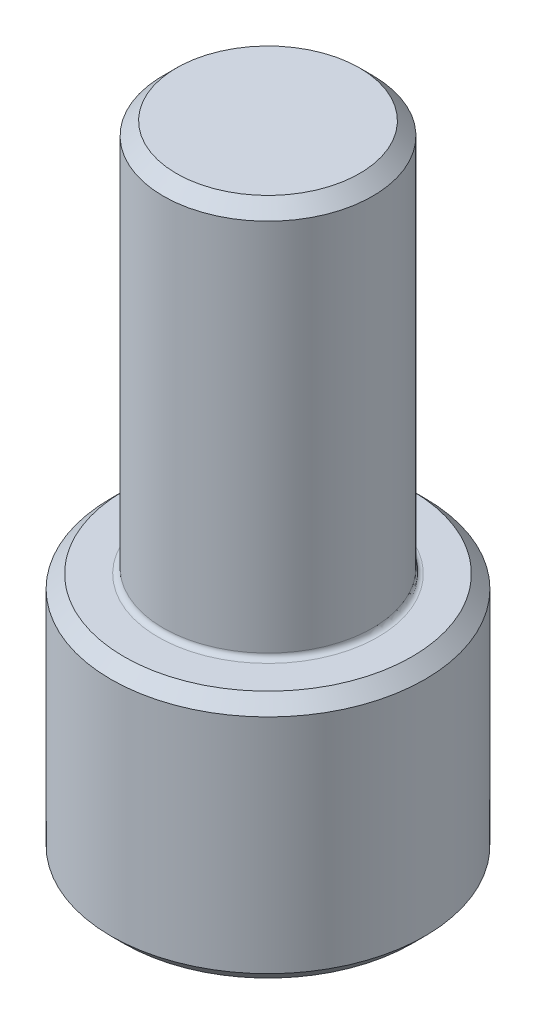
SolidWorks part; units mm, degrees
ref_plane "Front" through (0, 0, 0) normal (0, 0, 1) x (1, 0, 0)
ref_plane "Top" through (0, 0, 0) normal (0, 1, 0) x (1, 0, 0)
ref_plane "Right" through (0, 0, 0) normal (1, 0, 0) x (0, 0, -1)
sketch "Sketch1" plane through (0, 0, 0) normal (0, 0, 1) x (1, 0, 0)
  line L0 (0, 7.4762) -> (0, -8.3651) construction
  line L1 (0, 0) -> (6, 0)
  line L2 (6, 0) -> (6, 9.5)
  line L3 (6, 9.5) -> (4, 9.5)
  line L4 (4, 9.5) -> (4, 24.5)
  line L5 (4, 24.5) -> (0, 24.5)
  line L6 (0, 24.5) -> (0, 0)
  dimension "D1" = 9.5
  dimension "D2" = 15
  dimension "D3" = 4
  dimension "D4" = 2
revolve "Revolve1" add sketch "Sketch1" angle 360 about L0
hole_wizard "M4 Tapped Hole1" positions "Sketch2" profile "Sketch4" tap size "M4" standard "ISO"
sketch "Sketch2" plane through (0, 0, 0) normal (0, -1, 0) x (-1, 0, 0)
  point P0 (0, 0)
sketch "Sketch4" plane through (0, 0, 0) normal (1, 0, 0) x (0, 0, -1)
  line L0 (0, 0) -> (0, 11.0914)
  line L1 (0, 11.0914) -> (1.65, 10.1)
  line L2 (1.65, 10.1) -> (1.65, 0)
  line L5 (1.65, 0) -> (0, 0)
  line L10 (0, 11.0914) -> (-1.65, 10.1) construction
  line L11 (0, -6.35) -> (0, 107.95) construction
  dimension "Tap Drill Dia." = 3.3
  dimension "Tap Drill Depth" = 10.1
  dimension "Drill Angle" = 118
cosmetic thread "Hole Thread1" parameters "D1"=8, "D2"=4
fillet "Fillet1" radius 0.2 1 edges at (0, 9.5, 4)
chamfer "Chamfer1" distance 0.5 angle 45 3 edges at (0, 0, 6) (0, 9.5, 6) (0, 24.5, 4)
